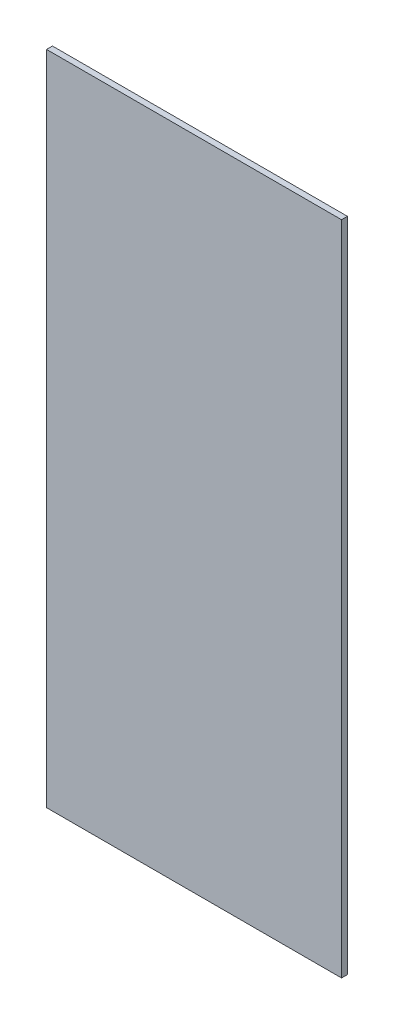
SolidWorks part; units mm, degrees
ref_plane "Спереди" through (0, 0, 0) normal (0, 0, 1) x (1, 0, 0)
ref_plane "Сверху" through (0, 0, 0) normal (0, 1, 0) x (1, 0, 0)
ref_plane "Справа" through (0, 0, 0) normal (1, 0, 0) x (0, 0, -1)
other "Configuration Table"
sketch "Эскиз2" plane through (0, 0, 0) normal (0, 0, 1) x (1, 0, 0)
  line L1 (0, 0) -> (1000, 0)
  line L2 (0, 0) -> (0, 2226)
  line L3 (0, 2226) -> (1000, 2226)
  line L4 (1000, 0) -> (1000, 2226)
  dimension "D1" = 1000
  dimension "D2" = 2226
extrude "Бобышка-Вытянуть1" add sketch "Эскиз2" along normal blind 20
